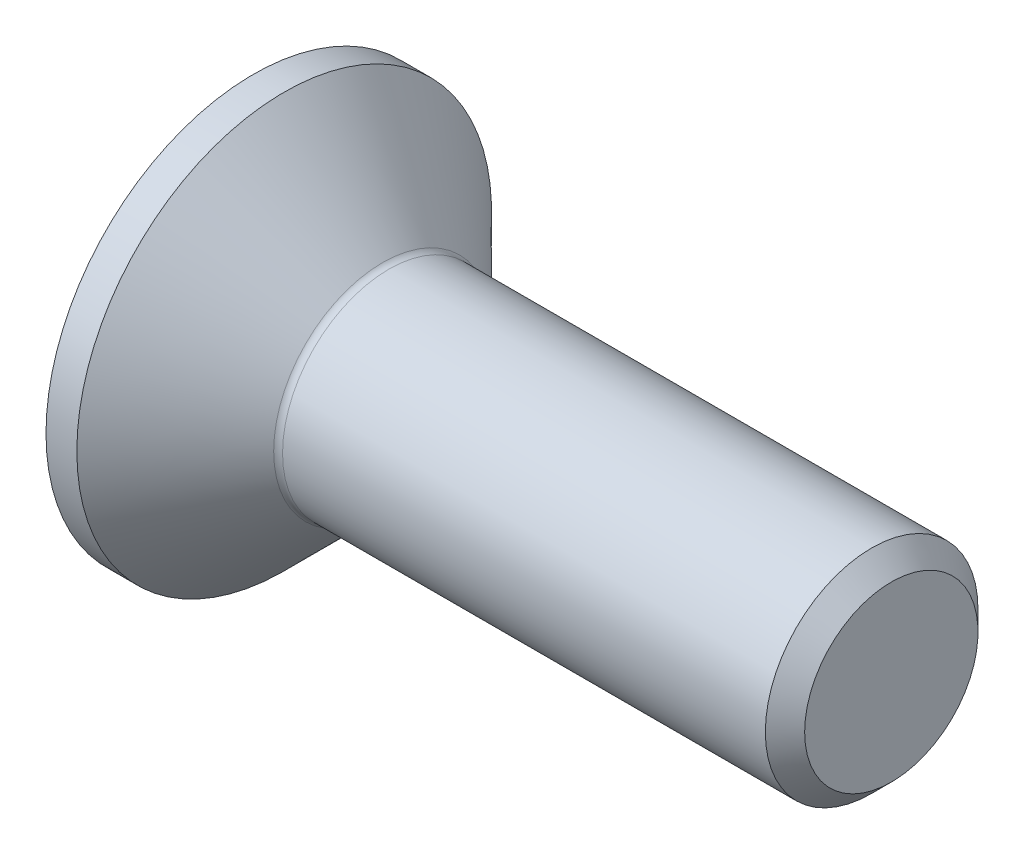
SolidWorks part; units mm, degrees
ref_plane "Plane1" through (0, 0, 0) normal (0, 0, 1) x (1, 0, 0)
ref_plane "Plane2" through (0, 0, 0) normal (0, 1, 0) x (1, 0, 0)
ref_plane "Plane3" through (0, 0, 0) normal (1, 0, 0) x (0, 0, -1)
sketch "BodySke" plane through (0, 0, 0) normal (0, 0, 1) x (1, 0, 0)
  line L0 (0, 0) -> (0, 5.85)
  line L1 (0.87, 5.85) -> (3.72, 3)
  line L2 (0, 5.85) -> (0.87, 5.85)
  line L3 (3.72, 3) -> (17.4455, 3)
  line L4 (18, 2.4455) -> (18, 0)
  line L5 (18, 0) -> (0, 0)
  line L6 (0, 0) -> (127, 0) construction
  line L7 (0.87, -5.85) -> (3.72, -3) construction
  line L8 (18, 2.4455) -> (17.4455, 3)
  line L9 (0, -5.85) -> (0.87, -5.85) construction
  line L10 (18, -2.4455) -> (17.4455, -3) construction
  line L11 (4.72, 9.35) -> (4.72, -12.875) construction
  line L12 (-2, 19.05) -> (-2, -3.175) construction
  dimension "D1" = 0.87
  dimension "Diameter" = 6
  dimension "Head_ht" = 3.72
  dimension "Length" = 18
  dimension "Body_ch_ang" = 45
  dimension "Head_dia" = 11.7
  dimension "Minor_dia" = 4.891
  dimension "Head_ang" = 90
  dimension "Advance" = 1
  dimension "Thread_nom" = 20
revolve "BaseBody" add sketch "BodySke" angle 360 about L6
cosmetic thread "ThreadCosmetic" parameters "Thread_length"=14.28, "Thread_minor"=4.891
fillet "Fillet1" radius 0.25 1 edges at (3.72, 0, 3)
sketch "Sketch2" plane through (0, 0, 0) normal (0, 0, 1) x (1, 0, 0)
  line L0 (0, 2) -> (2.2, 2)
  line L1 (2.2, 2) -> (3.3547, 0)
  line L2 (0, 0) -> (127, 0) construction
  line L3 (3.3547, 0) -> (0, 0)
  line L4 (0, 0) -> (0, 2)
  line L5 (0, -2) -> (2.2, -2) construction
  line L6 (0, 0) -> (47.625, 0) construction
  line L8 (0, 5.85) -> (0, -5.85) construction
  dimension "D2" = 60
  dimension "PreBroach_depth" = 2.2
  dimension "PreBroach_dia" = 4
revolve "PreBroach" cut sketch "Sketch2" angle 360 about L6
sketch "Sketch3" plane through (0, 0, 0) normal (-1, 0, 0) x (0, 0, 1)
  line L0 (-2, -1.1547) -> (-2, 1.1547)
  line L1 (-2, 1.1547) -> (0, 2.3094)
  line L2 (0, 2.3094) -> (2, 1.1547)
  line L3 (2, 1.1547) -> (2, -1.1547)
  line L4 (2, -1.1547) -> (0, -2.3094)
  line L5 (0, -2.3094) -> (-2, -1.1547)
  dimension "D1" = 2
  dimension "D2" = 2
  dimension "D3" = 4
  dimension "Hex_size" = 4
extrude "Hex" cut sketch "Sketch3" against normal blind 2.2
